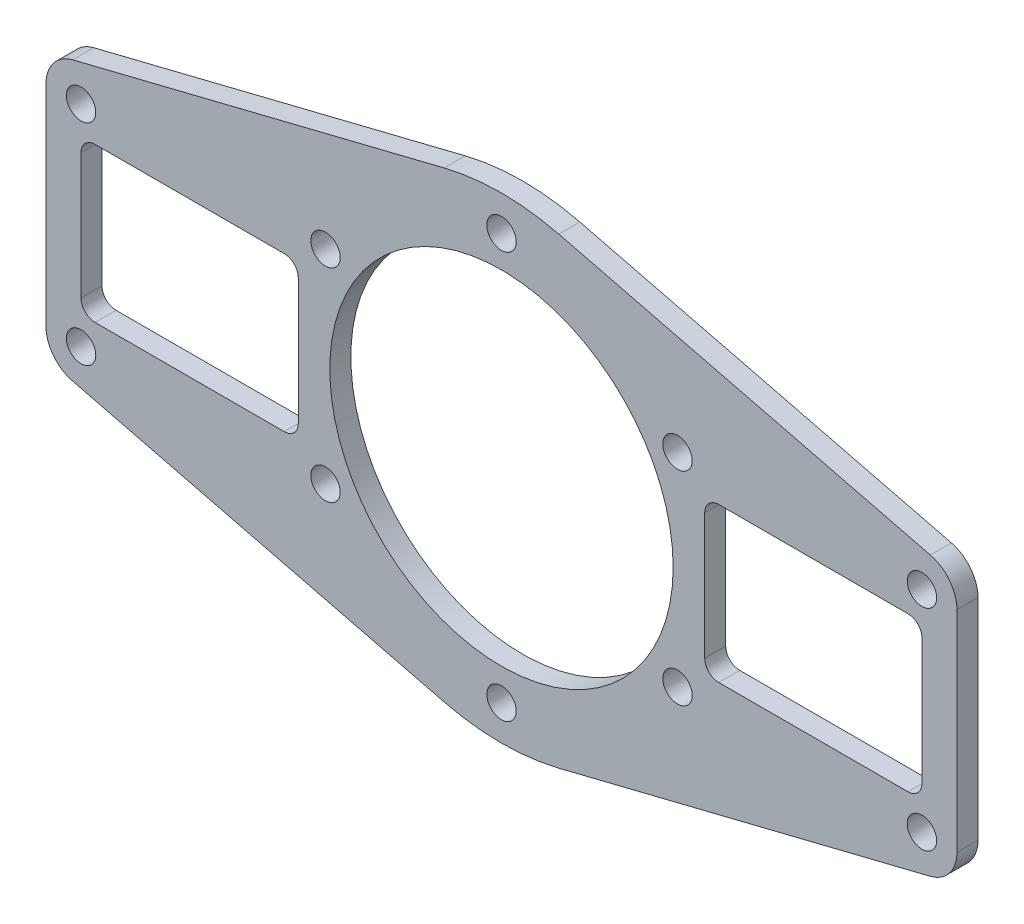
SolidWorks part; units mm, degrees
material "Thornel Mat VMA"
ref_plane "前视基准面" through (0, 0, 0) normal (0, 0, 1) x (1, 0, 0)
ref_plane "上视基准面" through (0, 0, 0) normal (0, 1, 0) x (1, 0, 0)
ref_plane "右视基准面" through (0, 0, 0) normal (1, 0, 0) x (0, 0, -1)
sketch "草图1" plane through (0, 0, 0) normal (0, 0, 1) x (1, 0, 0)
  line L0 (-65, 15) -> (-65, -15)
  line L1 (60, -15) -> (-60, -15) construction
  line L2 (60, -15) -> (60, 15) construction
  line L3 (60, 15) -> (-60, 15) construction
  line L4 (-60, -15) -> (-60, 15) construction
  line L5 (60, -15) -> (-60, 15) construction
  line L6 (60, 15) -> (-60, -15) construction
  line L7 (-61.2034, -19.853) -> (-8.1832, -33.0005)
  line L8 (8.1832, -33.0005) -> (61.2034, -19.853)
  line L9 (65, -15) -> (65, 15)
  line L10 (61.2034, 19.853) -> (8.1832, 33.0005)
  line L11 (-8.1832, 33.0005) -> (-61.2034, 19.853)
  circle A0 centre (0, 0) radius 24.5
  circle A1 centre (0, 0) radius 29 construction
  circle A2 centre (0, 29) radius 2.1
  circle A3 centre (25.1147, 14.5) radius 2.1
  circle A4 centre (25.1147, -14.5) radius 2.1
  circle A5 centre (0, -29) radius 2.1
  circle A6 centre (-25.1147, -14.5) radius 2.1
  circle A7 centre (-25.1147, 14.5) radius 2.1
  circle A8 centre (-60, 15) radius 2.1
  circle A9 centre (-60, -15) radius 2.1
  circle A10 centre (60, -15) radius 2.1
  circle A11 centre (60, 15) radius 2.1
  arc A12 (-8.1832, -33.0005) -> (8.1832, -33.0005) centre (0, 0) ccw
  arc A13 (8.1832, 33.0005) -> (-8.1832, 33.0005) centre (0, 0) ccw
  arc A14 (65, 15) -> (61.2034, 19.853) centre (60, 15) ccw
  arc A15 (61.2034, -19.853) -> (65, -15) centre (60, -15) ccw
  arc A16 (-65, -15) -> (-61.2034, -19.853) centre (-60, -15) ccw
  arc A17 (-65, 15) -> (-61.2034, 19.853) centre (-60, 15) cw
  point P18 (0, 0)
  dimension "D1" = 49
  dimension "D2" = 58
  dimension "D3" = 4.2
  dimension "D5" = 4.2
  dimension "D8" = 34
  dimension "D9" = 5
  dimension "D6" = 30
  dimension "D7" = 120
  dimension "D4" = 6
extrude "凸台-拉伸1" add sketch "草图1" along normal blind 3
sketch "草图2" plane through (0, 0, 3) normal (0, 0, 1) x (1, 0, 0)
  line L0 (29, 0) -> (-29, 0) construction
  line L1 (-58, 11) -> (-31, 11)
  line L2 (-60, 9) -> (-60, -9)
  line L3 (-58, -11) -> (-31, -11)
  line L4 (-29, 9) -> (-29, -9)
  line L5 (31, 11) -> (58, 11)
  line L6 (29, 9) -> (29, -9)
  line L7 (31, -11) -> (58, -11)
  line L8 (60, 9) -> (60, -9)
  line L9 (-65, 15) -> (-65, -15) construction
  arc A0 (58, 11) -> (60, 9) centre (58, 9) cw
  arc A1 (29, -9) -> (31, -11) centre (31, -9) ccw
  arc A2 (58, -11) -> (60, -9) centre (58, -9) ccw
  arc A3 (31, 11) -> (29, 9) centre (31, 9) ccw
  arc A4 (-31, 11) -> (-29, 9) centre (-31, 9) cw
  arc A5 (-60, -9) -> (-58, -11) centre (-58, -9) ccw
  arc A6 (-31, -11) -> (-29, -9) centre (-31, -9) ccw
  arc A7 (-58, 11) -> (-60, 9) centre (-58, 9) ccw
  point P25 (-60, -11)
  point P30 (-60, 11)
  dimension "D4" = 2
  dimension "D5" = 2
  dimension "D1" = 58
  dimension "D2" = 5
  dimension "D3" = 22
extrude "切除-拉伸1" cut sketch "草图2" against normal blind 10
